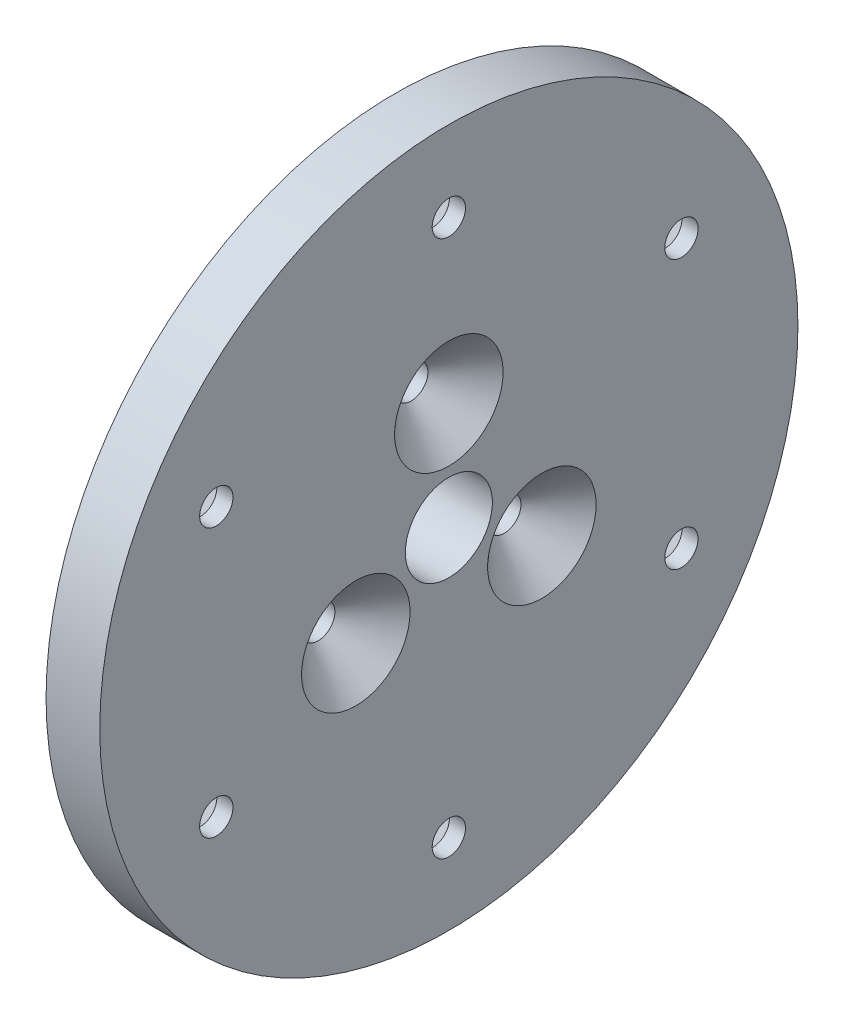
SolidWorks part; units mm, degrees
ref_plane "Ebene vorne" through (0, 0, 0) normal (0, 0, 1) x (1, 0, 0)
ref_plane "Ebene oben" through (0, 0, 0) normal (0, 1, 0) x (1, 0, 0)
ref_plane "Ebene rechts" through (0, 0, 0) normal (1, 0, 0) x (0, 0, -1)
sketch "Skizze1" plane through (0, 0, 0) normal (0, 0, 1) x (1, 0, 0)
  line L0 (0, 0) -> (-12136.2511, 0) construction
  line L1 (0, 0) -> (0, 16.5)
  line L2 (0, 16.5) -> (3, 16.5)
  line L3 (3, 16.5) -> (3, 32.5)
  line L4 (3, 32.5) -> (8, 32.5)
  line L5 (8, 32.5) -> (8, 0)
  line L6 (8, 0) -> (0, 0)
  dimension "D1" = 3
  dimension "D2" = 33
  dimension "D3" = 65
  dimension "D4" = 5
revolve "Rotation1" add sketch "Skizze1" angle 360 about L0
hole_wizard "Ø8.1 (8.1) Durchmesser Bohrung1" positions "Skizze2" profile "Skizze3" hole size "Ø8.1" standard "ISO" end condition through all
sketch "Skizze2" plane through (0, 0, 0) normal (-1, 0, 0) x (0, 0, 1)
  point P2 (0, 0)
sketch "Skizze3" plane through (0, 0, 0) normal (0, 1, 0) x (0, 0, 1)
  line L0 (0, 0) -> (0, 8)
  line L1 (0, 8) -> (4.05, 8)
  line L2 (4.05, 8) -> (4.05, 0)
  line L5 (4.05, 0) -> (0, 0)
  line L11 (0, -6.35) -> (0, 107.95) construction
  dimension "Bohrerdurchmesser" = 8.1
  dimension "Bohrungstiefe" = 8
sketch "Skizze4" plane through (8, 0, 0) normal (1, 0, 0) x (0, 0, -1)
  line L0 (0, 0) -> (0, 50000) construction
  circle A0 centre (0, 0) radius 10 construction
  circle A1 centre (0, 10) radius 1.55
  circle A2 centre (8.6603, -5) radius 1.55
  circle A3 centre (-8.6603, -5) radius 1.55
  point P15 (0, 0)
  dimension "D1" = 20
  dimension "D2" = 3.1
  dimension "D3" = 3
extrude "Schnitt-Linear austragen1" cut sketch "Skizze4" against normal through all
chamfer "Fase1" distance 3.5 angle 45 3 edges at (8, -5, -10.2103) (8, -5, 7.1103) (8, 10, -1.55)
sketch "Skizze5" plane through (8, 0, 0) normal (1, 0, 0) x (0, 0, -1)
  line L0 (0, 0) -> (0, -50000) construction
  circle A0 centre (0, 0) radius 25 construction
  circle A1 centre (0, 25) radius 1.55
  circle A2 centre (21.6506, 12.5) radius 1.55
  circle A3 centre (21.6506, -12.5) radius 1.55
  circle A4 centre (0, -25) radius 1.55
  circle A5 centre (-21.6506, -12.5) radius 1.55
  circle A6 centre (-21.6506, 12.5) radius 1.55
  point P20 (0, 0)
  dimension "D1" = 3.1
  dimension "D2" = 50
  dimension "D3" = 6
extrude "Schnitt-Linear austragen2" cut sketch "Skizze5" against normal through all
chamfer "Fase2" distance 3.5 angle 45 6 edges at (3, -12.5, -20.1006) (3, -25, 1.55) (3, -12.5, 23.2006) (3, 12.5, 23.2006) (3, 25, 1.55) (3, 12.5, -20.1006)
